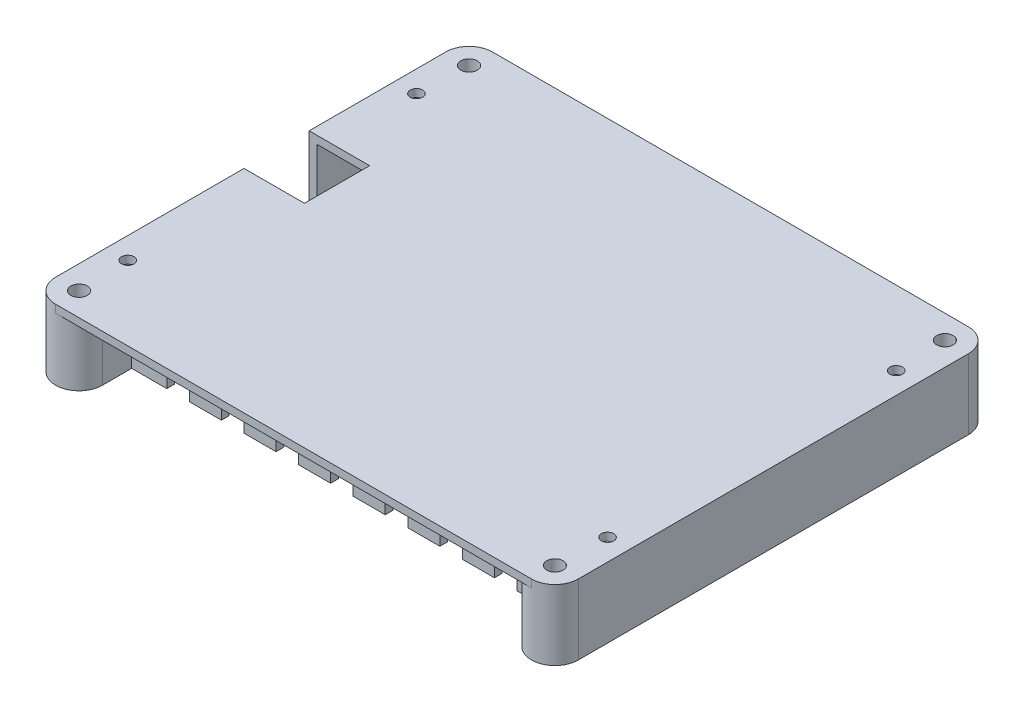
SolidWorks part; units mm, degrees
ref_plane "前视基准面" through (0, 0, 0) normal (0, 0, 1) x (1, 0, 0)
ref_plane "上视基准面" through (0, 0, 0) normal (0, 1, 0) x (1, 0, 0)
ref_plane "右视基准面" through (0, 0, 0) normal (1, 0, 0) x (0, 0, -1)
other "Configuration Table"
sketch "草图1" plane through (0, 0, 0) normal (0, 1, 0) x (1, 0, 0)
  line L1 (41.7763, -10) -> (41.7763, -2.5)
  line L24 (31.7763, -0.5) -> (161.7763, -0.5)
  line L25 (161.7763, -0.5) -> (161.7763, 80.5)
  line L27 (31.7763, 80.5) -> (31.7763, -0.5)
  line L32 (29.7763, 90) -> (29.7763, -10)
  line L34 (163.7763, -10) -> (163.7763, 90)
  line L44 (41.7763, -2.5) -> (151.7763, -2.5)
  line L46 (31.7763, -2.5) -> (161.7763, -2.5) construction
  line L47 (151.7763, -10) -> (151.7763, -2.5)
  line L49 (31.7763, 80.5) -> (35.7763, 80.5)
  line L51 (35.7763, 96) -> (157.7763, 96)
  line L52 (35.7763, 80.5) -> (35.7763, 84)
  line L53 (96.7763, 94) -> (40.2484, 94)
  line L54 (96.7763, 94) -> (153.3041, 94)
  line L55 (157.7763, 80.5) -> (157.7763, 84)
  line L56 (157.7763, 80.5) -> (161.7763, 80.5)
  arc A7 (35.7763, -16) -> (41.7763, -10) centre (35.7763, -10) ccw
  arc A9 (157.7763, -16) -> (151.7763, -10) centre (157.7763, -10) cw
  arc A17 (29.7763, -10) -> (35.7763, -16) centre (35.7763, -10) ccw
  arc A18 (157.7763, -16) -> (163.7763, -10) centre (157.7763, -10) ccw
  circle A25 centre (35.7763, -10) radius 2.1
  circle A27 centre (35.7763, 90) radius 2.1
  circle A29 centre (157.7763, 90) radius 2.1
  circle A31 centre (157.7763, -10) radius 2.1
  arc A32 (35.7763, 96) -> (29.7763, 90) centre (35.7763, 90) ccw
  arc A33 (153.3041, 94) -> (157.7763, 84) centre (157.7763, 90) ccw
  arc A34 (163.7763, 90) -> (157.7763, 96) centre (157.7763, 90) ccw
  arc A35 (35.7763, 84) -> (40.2484, 94) centre (35.7763, 90) ccw
  point P29 (31.7763, 40)
  point P30 (161.7763, 40)
  dimension "D2" = 2
extrude "凸台-拉伸1" add sketch "草图1" along normal blind 16
sketch "草图2" plane through (0, 16, 0) normal (0, 1, 0) x (1, 0, 0)
  line L6 (29.7763, 90) -> (29.7763, -10)
  line L7 (41.7763, -10) -> (41.7763, -2.5)
  line L8 (41.7763, -2.5) -> (151.7763, -2.5)
  line L9 (151.7763, -2.5) -> (151.7763, -10)
  line L10 (163.7763, -10) -> (163.7763, 90)
  line L11 (157.7763, 96) -> (35.7763, 96)
  line L12 (29.7763, 90) -> (29.7763, -10)
  line L13 (41.7763, -10) -> (41.7763, -2.5)
  line L14 (41.7763, -2.5) -> (151.7763, -2.5)
  line L15 (151.7763, -2.5) -> (151.7763, -10)
  line L16 (163.7763, -10) -> (163.7763, 90)
  line L17 (157.7763, 96) -> (35.7763, 96)
  circle A0 centre (35.7763, 90) radius 2.1 construction
  circle A1 centre (35.7763, 90) radius 2.1
  circle A2 centre (157.7763, 90) radius 2.1 construction
  circle A3 centre (157.7763, 90) radius 2.1
  arc A4 (35.7763, 96) -> (29.7763, 90) centre (35.7763, 90) ccw
  arc A5 (29.7763, -10) -> (41.7763, -10) centre (35.7763, -10) ccw
  arc A6 (151.7763, -10) -> (163.7763, -10) centre (157.7763, -10) ccw
  arc A7 (163.7763, 90) -> (157.7763, 96) centre (157.7763, 90) ccw
  arc A8 (35.7763, 96) -> (29.7763, 90) centre (35.7763, 90) ccw
  arc A9 (29.7763, -10) -> (41.7763, -10) centre (35.7763, -10) ccw
  arc A10 (151.7763, -10) -> (163.7763, -10) centre (157.7763, -10) ccw
  arc A11 (163.7763, 90) -> (157.7763, 96) centre (157.7763, 90) ccw
  circle A12 centre (35.7763, -10) radius 2.1 construction
  circle A13 centre (35.7763, -10) radius 2.1
  circle A14 centre (157.7763, -10) radius 2.1 construction
  circle A15 centre (157.7763, -10) radius 2.1
  dimension "D1" = 0
extrude "凸台-拉伸2" add sketch "草图2" along normal blind 2
sketch "草图3" plane through (0, 18, 0) normal (0, 1, 0) x (1, 0, 0)
  line L0 (41.7763, -2.5) -> (151.7763, -2.5) construction
  line L1 (41.7763, -2.5) -> (151.7763, -2.5)
  line L2 (41.7763, -10) -> (41.7763, -2.5) construction
  line L3 (41.7763, -10) -> (41.7763, -2.5)
  line L4 (151.7763, -2.5) -> (151.7763, -10) construction
  line L5 (151.7763, -2.5) -> (151.7763, -10)
  line L6 (35.7763, -16) -> (157.7763, -16)
  arc A0 (29.7763, -10) -> (41.7763, -10) centre (35.7763, -10) ccw construction
  arc A1 (35.7763, -16) -> (41.7763, -10) centre (35.7763, -10) ccw
  arc A2 (151.7763, -10) -> (163.7763, -10) centre (157.7763, -10) ccw construction
  arc A3 (151.7763, -10) -> (157.7763, -16) centre (157.7763, -10) ccw
extrude "凸台-拉伸3" add sketch "草图3" against normal blind 2
sketch "草图4" plane through (0, 0, 2.5) normal (0, 0, 1) x (1, 0, 0)
  line L0 (64.7763, 0) -> (64.7763, 13.4)
  line L1 (41.7763, 0) -> (151.7763, 0) construction
  line L2 (50.7763, 0) -> (50.7763, 13.4)
  line L3 (50.7763, 13.4) -> (56.5763, 13.4)
  line L4 (56.5763, 13.4) -> (56.5763, 0)
  line L5 (56.5763, 0) -> (50.7763, 0)
  line L6 (64.7763, 13.4) -> (70.5763, 13.4)
  line L7 (70.5763, 13.4) -> (70.5763, 0)
  line L8 (70.5763, 0) -> (64.7763, 0)
  line L9 (78.7763, 0) -> (78.7763, 13.4)
  line L10 (78.7763, 13.4) -> (84.5763, 13.4)
  line L11 (84.5763, 13.4) -> (84.5763, 0)
  line L12 (84.5763, 0) -> (78.7763, 0)
  line L13 (92.7763, 0) -> (92.7763, 13.4)
  line L14 (92.7763, 13.4) -> (98.5763, 13.4)
  line L15 (98.5763, 13.4) -> (98.5763, 0)
  line L16 (98.5763, 0) -> (92.7763, 0)
  line L17 (106.7763, 0) -> (106.7763, 13.4)
  line L18 (106.7763, 13.4) -> (112.5763, 13.4)
  line L19 (112.5763, 13.4) -> (112.5763, 0)
  line L20 (112.5763, 0) -> (106.7763, 0)
  line L21 (120.7763, 0) -> (120.7763, 13.4)
  line L22 (120.7763, 13.4) -> (126.5763, 13.4)
  line L23 (126.5763, 13.4) -> (126.5763, 0)
  line L24 (126.5763, 0) -> (120.7763, 0)
  line L25 (134.7763, 0) -> (134.7763, 13.4)
  line L26 (134.7763, 13.4) -> (140.5763, 13.4)
  line L27 (140.5763, 13.4) -> (140.5763, 0)
  line L28 (140.5763, 0) -> (134.7763, 0)
  dimension "D1" = 7
extrude "切除-拉伸1" cut sketch "草图4" against normal blind 2
sketch "草图5" plane through (29.7763, 0, 0) normal (-1, 0, 0) x (0, 0, 1)
  line L1 (-90, 0) -> (10, 0) construction
  line L2 (-18.5, 0) -> (-18.5, 11)
  line L3 (-18.5, 11) -> (-27.5, 11)
  line L4 (-27.5, 11) -> (-27.5, 0)
  line L5 (-27.5, 0) -> (-18.5, 0)
extrude "切除-拉伸2" cut sketch "草图5" against normal blind 2
sketch "草图6" plane through (29.7763, 0, 0) normal (-1, 0, 0) x (0, 0, 1)
  line L1 (-90, 0) -> (-27.5, 0) construction
  line L2 (-38.3, 0) -> (-55, 0)
  line L3 (-55, 0) -> (-55, 18)
  line L4 (-90, 18) -> (10, 18) construction
  line L5 (-55, 18) -> (-38.3, 18)
  line L6 (-38.3, 18) -> (-38.3, 0)
extrude "切除-拉伸3" cut sketch "草图6" against normal blind 15.5
sketch "草图7" plane through (0, 18, 0) normal (0, 1, 0) x (1, 0, 0)
  circle A0 centre (158.2763, 77) radius 1.6
  circle A1 centre (35.2763, 77) radius 1.6
  circle A2 centre (35.2763, 3) radius 1.6
  circle A3 centre (158.2763, 3) radius 1.6
extrude "切除-拉伸4" cut sketch "草图7" against normal blind 2
